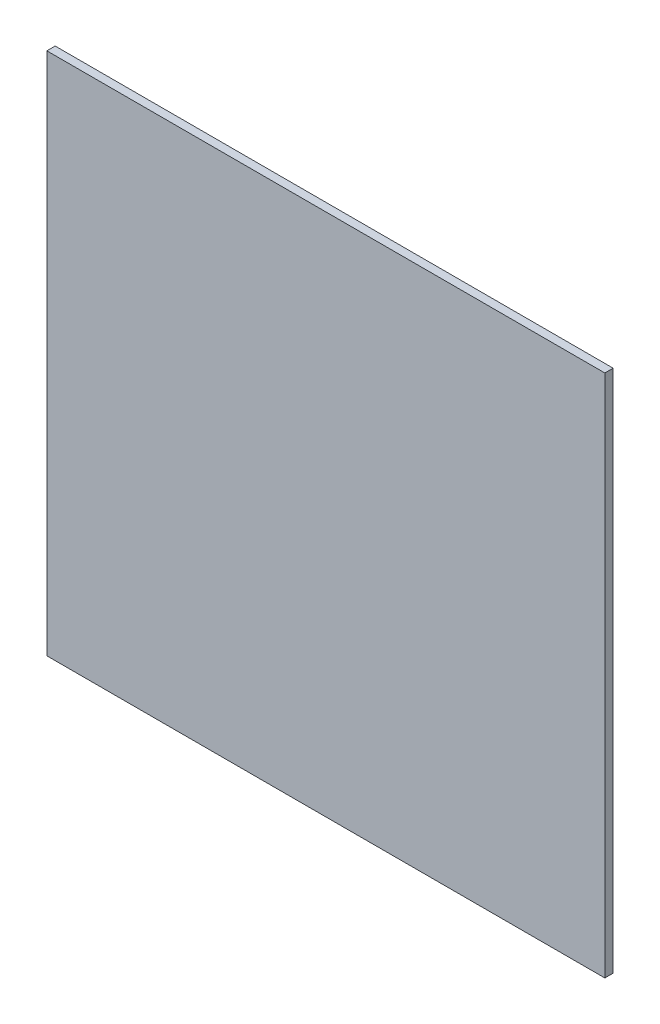
SolidWorks part; units mm, degrees
material "Glass"
ref_plane "Front Plane" through (0, 0, 0) normal (0, 0, 1) x (1, 0, 0)
ref_plane "Top Plane" through (0, 0, 0) normal (0, 1, 0) x (1, 0, 0)
ref_plane "Right Plane" through (0, 0, 0) normal (1, 0, 0) x (0, 0, -1)
sketch "Sketch1" plane through (0, 0, 0) normal (0, 0, 1) x (1, 0, 0)
  line L0 (106.5, 100) -> (-106.5, -100) construction
  line L1 (-106.5, 100) -> (106.5, 100)
  line L2 (-106.5, 100) -> (-106.5, -100)
  line L3 (-106.5, -100) -> (106.5, -100)
  line L4 (106.5, 100) -> (106.5, -100)
  dimension "D1" = 213
  dimension "D2" = 200
extrude "Boss-Extrude1" add sketch "Sketch1" along normal blind 3.175
